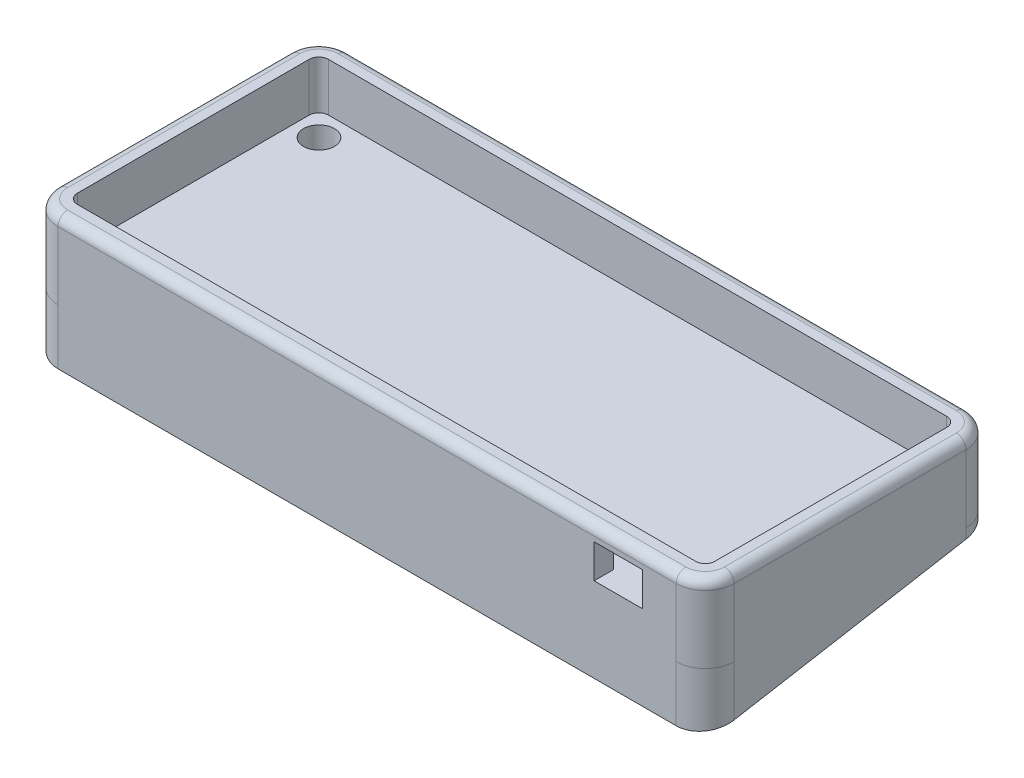
SolidWorks part; units mm, degrees
ref_plane "Front Plane" through (0, 0, 0) normal (0, 0, 1) x (1, 0, 0)
ref_plane "Top Plane" through (0, 0, 0) normal (0, 1, 0) x (1, 0, 0)
ref_plane "Right Plane" through (0, 0, 0) normal (1, 0, 0) x (0, 0, -1)
sketch "Sketch1" plane through (0, 0, 0) normal (0, 1, 0) x (1, 0, 0)
  line L0 (-61.6637, 44.4956) -> (66.3363, 44.4956)
  line L1 (-61.6637, 40.4956) -> (66.3363, 40.4956)
  line L2 (-63.6637, 38.4956) -> (-63.6637, -9.5044)
  line L3 (-61.6637, -11.5044) -> (66.3363, -11.5044)
  line L4 (68.3363, 38.4956) -> (68.3363, -9.5044)
  line L5 (72.3363, 38.4956) -> (72.3363, -9.5044)
  line L6 (-61.6637, -15.5044) -> (66.3363, -15.5044)
  line L7 (-67.6637, 38.4956) -> (-67.6637, -9.5044)
  line L8 (-63.6637, 40.4956) -> (68.3363, 40.4956) construction
  line L9 (68.3363, 40.4956) -> (68.3363, -11.5044) construction
  line L10 (-63.6637, 40.4956) -> (-63.6637, -11.5044) construction
  line L11 (-63.6637, -11.5044) -> (68.3363, -11.5044) construction
  line L12 (-67.6637, 44.4956) -> (72.3363, 44.4956) construction
  line L13 (72.3363, 44.4956) -> (72.3363, -15.5044) construction
  line L14 (-67.6637, -15.5044) -> (72.3363, -15.5044) construction
  line L15 (-67.6637, 44.4956) -> (-67.6637, -15.5044) construction
  arc A0 (66.3363, 40.4956) -> (68.3363, 38.4956) centre (66.3363, 38.4956) cw
  arc A1 (-63.6637, -9.5044) -> (-61.6637, -11.5044) centre (-61.6637, -9.5044) ccw
  arc A2 (66.3363, -11.5044) -> (68.3363, -9.5044) centre (66.3363, -9.5044) ccw
  arc A3 (-61.6637, 40.4956) -> (-63.6637, 38.4956) centre (-61.6637, 38.4956) ccw
  arc A4 (66.3363, 44.4956) -> (72.3363, 38.4956) centre (66.3363, 38.4956) cw
  arc A5 (72.3363, -9.5044) -> (66.3363, -15.5044) centre (66.3363, -9.5044) cw
  arc A6 (-61.6637, -15.5044) -> (-67.6637, -9.5044) centre (-61.6637, -9.5044) cw
  arc A7 (-67.6637, 38.4956) -> (-61.6637, 44.4956) centre (-61.6637, 38.4956) cw
  point P11 (68.3363, 40.4956)
  point P33 (0, 0)
  dimension "D4" = 2
  dimension "D1" = 6
  dimension "D3" = 4
extrude "Boss-Extrude1" add sketch "Sketch1" along normal blind 16
sketch "Sketch2" plane through (0, 0, 0) normal (0, 1, 0) x (1, 0, 0)
  line L0 (-63.6279, 40.4956) -> (-58.6279, 40.4956) construction
  line L1 (-61.6637, 40.4956) -> (66.3363, 40.4956)
  line L2 (-63.6637, 38.4956) -> (-63.6637, -9.5044)
  line L3 (-61.6637, -11.5044) -> (66.3363, -11.5044)
  line L4 (68.3363, 38.4956) -> (68.3363, -9.5044)
  line L5 (-58.6279, 40.4956) -> (-58.6279, 35.4956) construction
  line L6 (2.3363, 40.4956) -> (2.3363, -11.5044) construction
  line L7 (-63.6637, 14.4956) -> (68.3363, 14.4956) construction
  arc A0 (66.3363, 40.4956) -> (68.3363, 38.4956) centre (66.3363, 38.4956) cw
  arc A1 (-63.6637, -9.5044) -> (-61.6637, -11.5044) centre (-61.6637, -9.5044) ccw
  arc A2 (66.3363, -11.5044) -> (68.3363, -9.5044) centre (66.3363, -9.5044) ccw
  arc A3 (-61.6637, 40.4956) -> (-63.6637, 38.4956) centre (-61.6637, 38.4956) ccw
  circle A4 centre (-58.6279, 35.4956) radius 3.2
  circle A5 centre (63.3005, 35.4956) radius 3.2
  circle A6 centre (-58.6279, -6.5044) radius 3.2
  dimension "D1" = 2
  dimension "D2" = 5
  dimension "D3" = 5
extrude "Boss-Extrude2" add sketch "Sketch2" along normal blind 6
sketch "Sketch3" plane through (0, 0, 0) normal (0, 0, 1) x (1, 0, 0)
  line L1 (66.3363, 13) -> (59.3363, 13)
  line L2 (66.3363, 16) -> (66.3363, 0) construction
  line L3 (-61.6637, 0) -> (66.3363, 0) construction
  line L4 (59.3363, 13) -> (49.3363, 13)
  line L5 (59.3363, 13) -> (59.3363, 6)
  line L6 (59.3363, 6) -> (49.3363, 6)
  line L7 (49.3363, 13) -> (49.3363, 6)
  dimension "D1" = 7
  dimension "D2" = 10
  dimension "D3" = 7
  dimension "D4" = 6
extrude "Cut-Extrude1" cut sketch "Sketch3" along normal blind 28 contours L4 L7 L6 L5
fillet "Fillet2" radius 2 8 edges at (70.5789, 16, 13.7471) (2.3363, 16, 15.5044) (-65.9064, 16, 13.7471) (-67.6637, 16, -14.4956) (-65.9064, 16, -42.7382) (2.3363, 16, -44.4956) (70.5789, 16, -42.7382) (72.3363, 16, -14.4956)
sketch "Sketch4" plane through (72.3363, 0, 0) normal (1, 0, 0) x (0, 0, -1)
  line L0 (-15.5044, 0) -> (-15.5044, -11.5)
  line L2 (-15.5044, 0) -> (44.4956, 0)
  line L3 (44.4956, 0) -> (44.4956, -1)
  line L4 (-15.5044, -11.5) -> (44.4956, -1)
  dimension "D1" = 11.5
  dimension "D2" = 1
extrude "Boss-Extrude3" add sketch "Sketch4" against normal blind 140
fillet "Fillet3" radius 6 4 edges at (-67.6637, -5.75, 15.5044) (72.3363, -5.75, 15.5044) (-67.6637, -0.5, -44.4956) (72.3363, -0.5, -44.4956)
